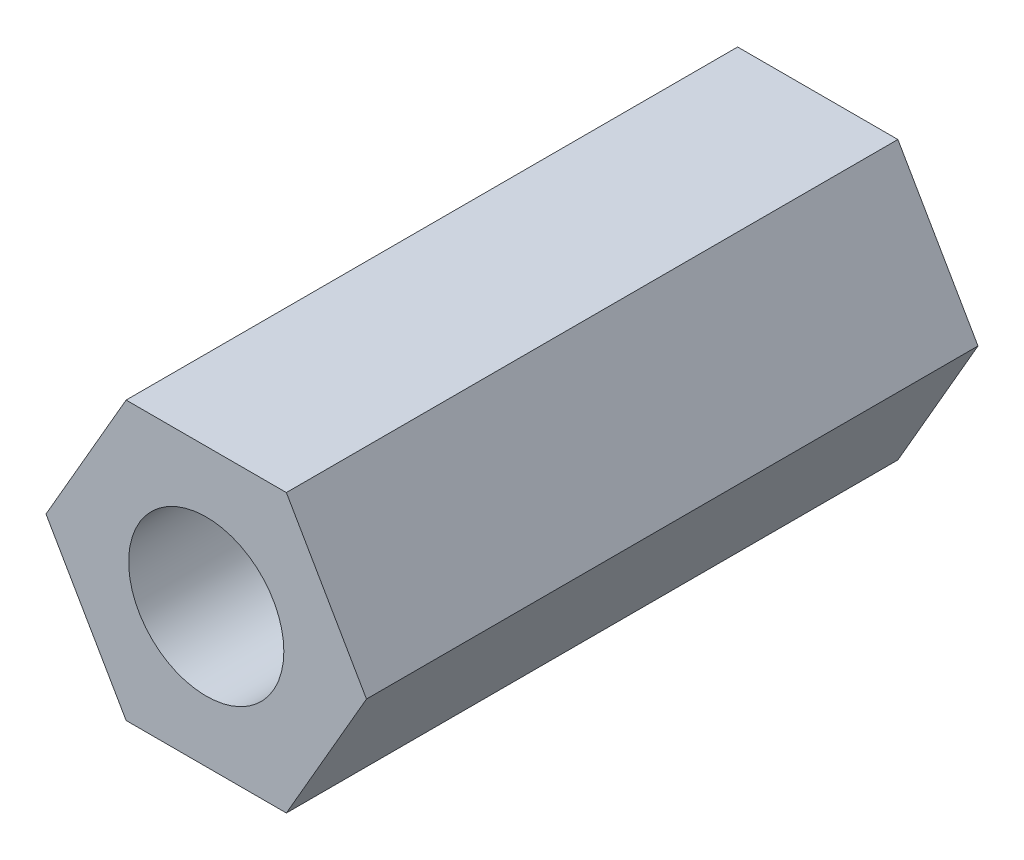
SolidWorks part; units mm, degrees
material "黄铜"
ref_plane "前视基准面" through (0, 0, 0) normal (0, 0, 1) x (1, 0, 0)
ref_plane "上视基准面" through (0, 0, 0) normal (0, 1, 0) x (1, 0, 0)
ref_plane "右视基准面" through (0, 0, 0) normal (1, 0, 0) x (0, 0, -1)
sketch "草图1" plane through (0, 0, 0) normal (0, 0, 1) x (1, 0, 0)
  line L1 (1.7032, 2.95) -> (-1.7032, 2.95)
  line L2 (-1.7032, 2.95) -> (-3.4064, 0)
  line L3 (-3.4064, 0) -> (-1.7032, -2.95)
  line L4 (-1.7032, -2.95) -> (1.7032, -2.95)
  line L5 (1.7032, -2.95) -> (3.4064, 0)
  line L6 (3.4064, 0) -> (1.7032, 2.95)
  circle A0 centre (0, 0) radius 2.95 construction
  dimension "D1" = 5.9
extrude "凸台-拉伸1" add sketch "草图1" along normal blind 13
hole_wizard "M4 螺纹孔1" positions "草图2" profile "草图3" tap size "M4" standard "GB" end condition through all
sketch "草图2" plane through (0, 0, 13) normal (0, 0, 1) x (1, 0, 0)
  point P0 (0, 0)
sketch "草图3" plane through (0, 0, 13) normal (1, 0, 0) x (0, -1, 0)
  line L0 (0, 0) -> (0, 13)
  line L1 (0, 13) -> (1.65, 13)
  line L2 (1.65, 13) -> (1.65, 0)
  line L5 (1.65, 0) -> (0, 0)
  line L11 (0, -6.35) -> (0, 107.95) construction
  dimension "通孔螺纹孔钻头直径" = 3.3
  dimension "通孔螺纹孔钻头深度" = 13
cosmetic thread "孔螺蚊线1"
move or copy body "实体-移动/复制1" [suppressed] bodies to move or copy 107
